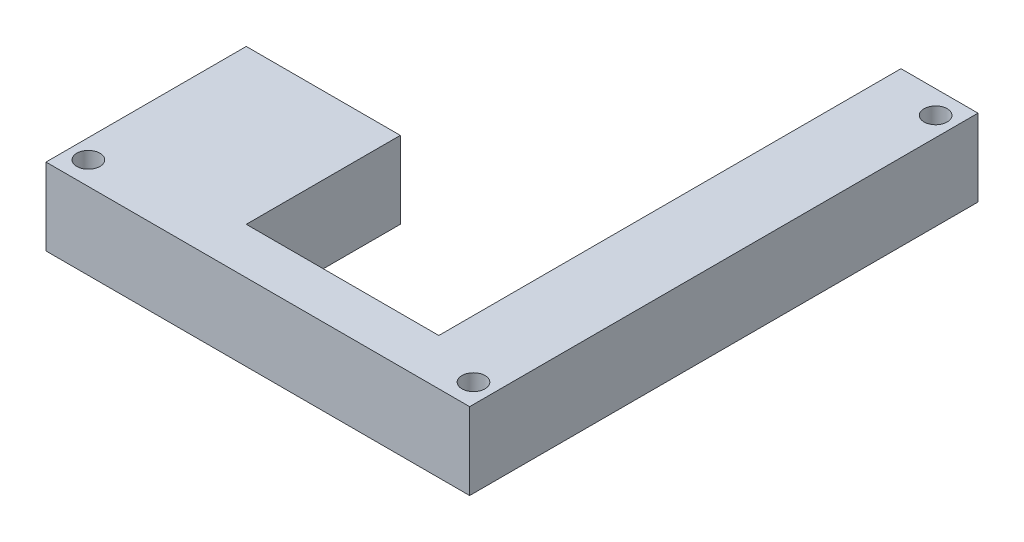
SolidWorks part; units mm, degrees
ref_plane "Plan de face" through (0, 0, 0) normal (0, 0, 1) x (1, 0, 0)
ref_plane "Plan de dessus" through (0, 0, 0) normal (0, 1, 0) x (1, 0, 0)
ref_plane "Plan de droite" through (0, 0, 0) normal (1, 0, 0) x (0, 0, -1)
sketch "Esquisse1" plane through (0, 0, 0) normal (0, 1, 0) x (1, 0, 0)
  line L0 (5.2888, 30.5081) -> (15.2888, 30.5081)
  line L1 (15.2888, 30.5081) -> (15.2888, -35.4919)
  line L2 (15.2888, -35.4919) -> (-39.7112, -35.4919)
  line L5 (5.2888, -29.4919) -> (5.2888, 30.5081)
  line L6 (-39.7112, -35.4919) -> (-39.7112, -9.4919)
  line L7 (-39.7112, -9.4919) -> (-19.7112, -9.4919)
  line L8 (-19.7112, -9.4919) -> (-19.7112, -29.4919)
  line L9 (-19.7112, -29.4919) -> (5.2888, -29.4919)
  line L10 (15.2888, -35.4919) -> (15.2888, -32.4919) construction
  line L11 (15.2888, -32.4919) -> (12.7888, -32.4919) construction
  line L12 (-39.7112, -35.4919) -> (-37.2112, -35.4919) construction
  line L13 (-37.2112, -35.4919) -> (-37.2112, -32.4919) construction
  line L14 (15.2888, 30.5081) -> (15.2888, 27.5081) construction
  line L15 (15.2888, 27.5081) -> (12.7888, 27.5081) construction
  circle A0 centre (12.7888, -32.4919) radius 1.5
  circle A1 centre (-37.2112, -32.4919) radius 1.5
  circle A2 centre (12.7888, 27.5081) radius 1.5
  dimension "D4" = 10
  dimension "D1" = 55
  dimension "D2" = 66
  dimension "D3" = 60
  dimension "D5" = 20
  dimension "D6" = 40
extrude "Boss.-Extru.1" add sketch "Esquisse1" along normal blind 10
